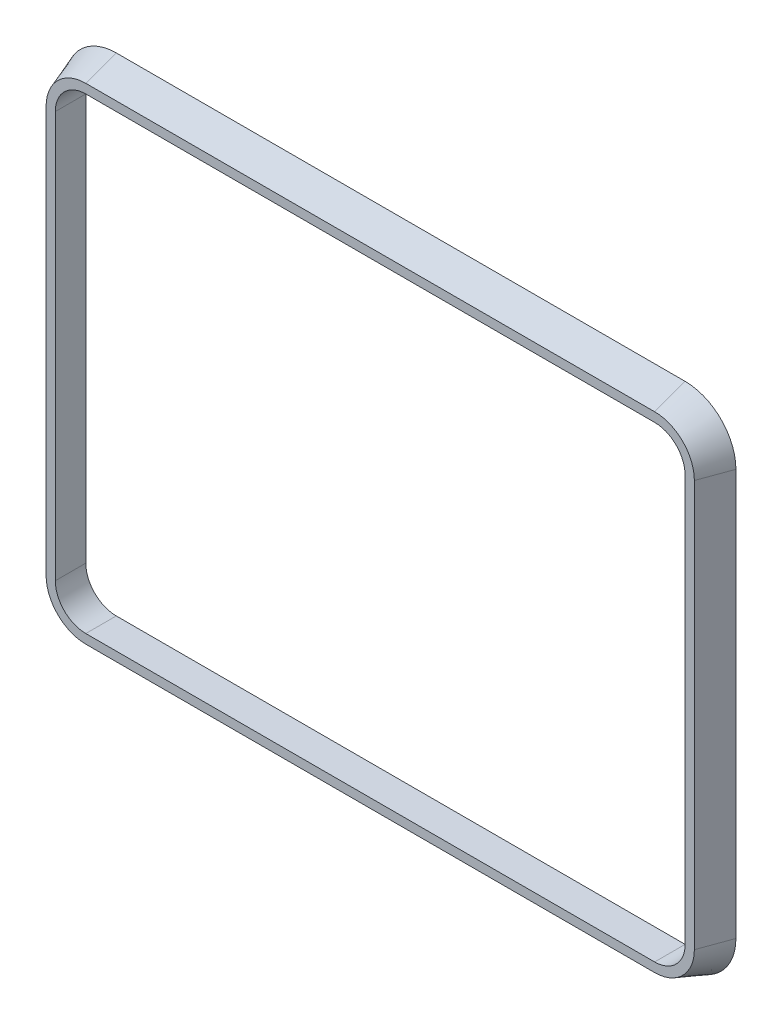
SolidWorks part; units mm, degrees
material "Silicon"
ref_plane "Front" through (0, 0, 0) normal (0, 0, 1) x (1, 0, 0)
ref_plane "Top" through (0, 0, 0) normal (0, 1, 0) x (1, 0, 0)
ref_plane "Right" through (0, 0, 0) normal (1, 0, 0) x (0, 0, -1)
sketch "Sketch1" plane through (0, 0, 0) normal (0, 0, 1) x (1, 0, 0)
  line L1 (-28, -25) -> (28, -25)
  line L2 (-33, -20) -> (-33, 20)
  line L3 (-28, 25) -> (28, 25)
  line L4 (33, -20) -> (33, 20)
  line L5 (-33, -25) -> (33, 25) construction
  line L6 (-33, 25) -> (33, -25) construction
  arc A0 (-28, -25) -> (-33, -20) centre (-28, -20) cw
  arc A1 (28, -25) -> (33, -20) centre (28, -20) ccw
  arc A2 (28, 25) -> (33, 20) centre (28, 20) cw
  arc A3 (-33, 20) -> (-28, 25) centre (-28, 20) cw
  point P0 (0, 0)
  dimension "D3" = 5
  dimension "D1" = 66
  dimension "D2" = 50
extrude "Boss-Extrude1" add sketch "Sketch1" along normal blind 3 draft 20
sketch "Sketch2" plane through (0, 0, 3) normal (0, 0, 1) x (1, 0, 0)
  line L5 (-28, -23) -> (28, -23)
  line L6 (-31, -20) -> (-31, 20)
  line L7 (-28, 23) -> (28, 23)
  line L8 (31, -20) -> (31, 20)
  line L9 (-31, -23) -> (31, 23) construction
  line L10 (-31, 23) -> (31, -23) construction
  arc A4 (-28, -23) -> (-31, -20) centre (-28, -20) cw
  arc A5 (28, -23) -> (31, -20) centre (28, -20) ccw
  arc A6 (28, 23) -> (31, 20) centre (28, 20) cw
  arc A7 (-31, 20) -> (-28, 23) centre (-28, 20) cw
  point P0 (0, 0)
  dimension "D3" = 3
  dimension "D1" = 46
  dimension "D2" = 62
extrude "Cut-Extrude1" cut sketch "Sketch2" against normal through all
